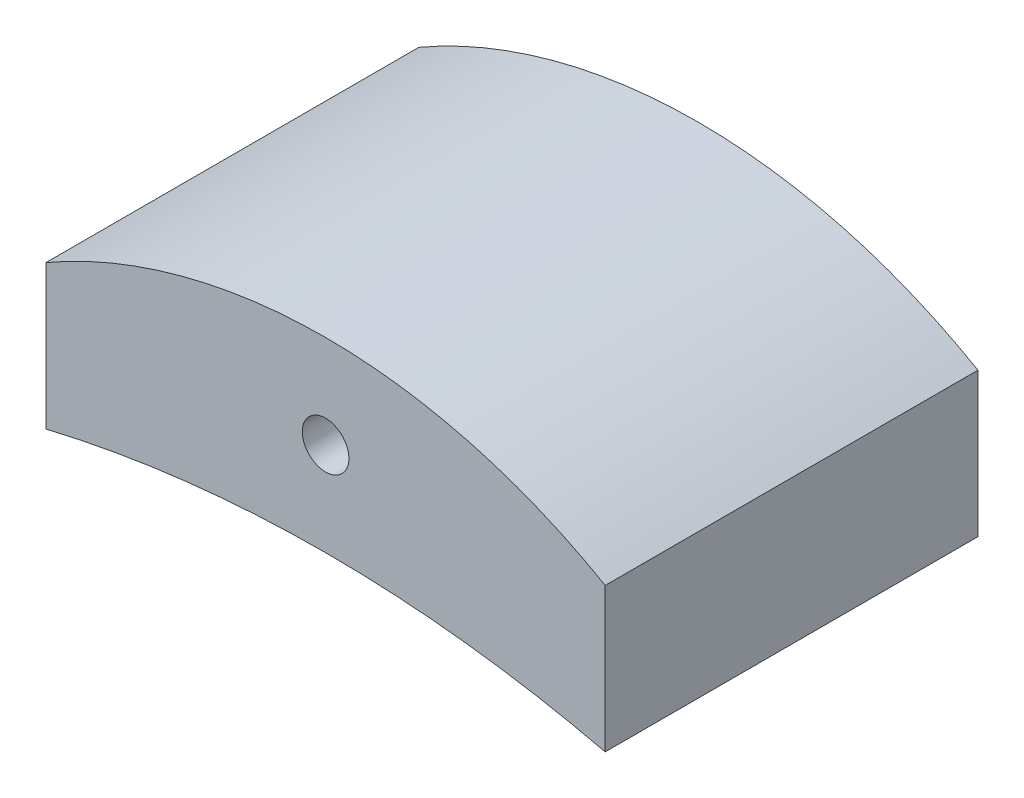
SolidWorks part; units mm, degrees
ref_plane "Front Plane" through (0, 0, 0) normal (0, 0, 1) x (1, 0, 0)
ref_plane "Top Plane" through (0, 0, 0) normal (0, 1, 0) x (1, 0, 0)
ref_plane "Right Plane" through (0, 0, 0) normal (1, 0, 0) x (0, 0, -1)
sketch "Sketch1" plane through (0, 0, 0) normal (0, 0, 1) x (1, 0, 0)
  line L1 (0, 0) -> (76.2, 0)
  line L2 (0, 0) -> (0, 152.4)
  line L3 (0, 152.4) -> (76.2, 152.4)
  line L4 (76.2, 0) -> (76.2, 152.4)
  circle A0 centre (38.1, 0) radius 76.2
  circle A1 centre (38.1, -114.3) radius 165.1
  circle A2 centre (38.1, 63.5) radius 3.175
  point P11 (0, 0)
  dimension "D3" = 152.4
  dimension "D4" = 330.2
  dimension "D7" = 6.35
  dimension "D1" = 76.2
  dimension "D2" = 152.4
  dimension "D5" = 38.1
  dimension "D6" = 114.3
  dimension "D10" = 63.5
  dimension "D12" = 38.1
extrude "Boss-Extrude2" add sketch "Sketch1" along normal blind 50.8
sketch "Sketch3" plane through (0, 0, 0) normal (0, 0, -1) x (-1, 0, 0)
  circle A0 centre (-25.4, 63.5) radius 4.7625
  circle A1 centre (-38.1, 63.5) radius 4.7625
  dimension "D1" = 9.525
  dimension "D2" = 9.525
extrude "Cut-Extrude2" cut sketch "Sketch3" against normal blind 38.1 contours A1
